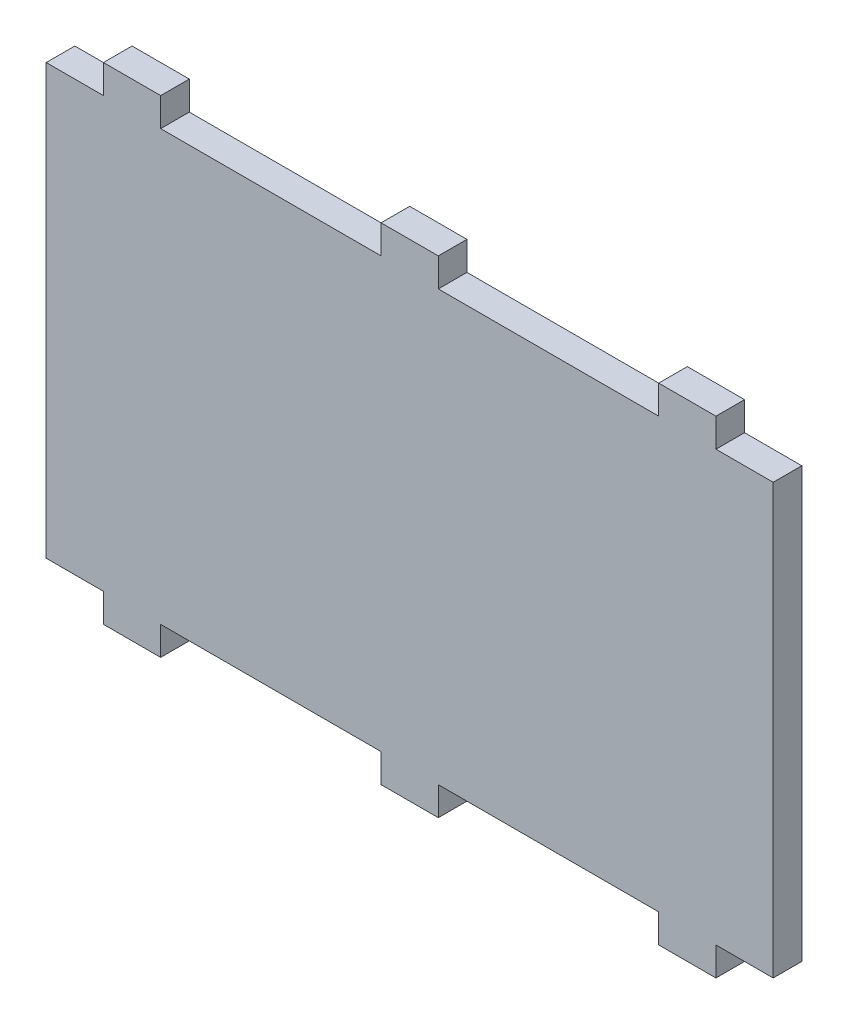
SolidWorks part; units mm, degrees
ref_plane "Plan de face" through (0, 0, 0) normal (0, 0, 1) x (1, 0, 0)
ref_plane "Plan de dessus" through (0, 0, 0) normal (0, 1, 0) x (1, 0, 0)
ref_plane "Plan de droite" through (0, 0, 0) normal (1, 0, 0) x (0, 0, -1)
sketch "Esquisse1" plane through (0, 0, 0) normal (0, 0, 1) x (1, 0, 0)
  line L1 (0, 0) -> (127, 0)
  line L2 (0, 0) -> (0, 75)
  line L3 (0, 75) -> (127, 75)
  line L4 (127, 0) -> (127, 75)
  dimension "D1" = 75
  dimension "D2" = 127
extrude "Boss.-Extru.1" add sketch "Esquisse1" along normal blind 5
sketch "Esquisse2" plane through (0, 0, 5) normal (0, 0, 1) x (1, 0, 0)
  line L0 (127, 75) -> (0, 75) construction
  line L1 (10, 75) -> (20, 75)
  line L2 (10, 75) -> (10, 80)
  line L3 (10, 80) -> (20, 80)
  line L4 (20, 75) -> (20, 80)
  line L5 (0, 0) -> (127, 0) construction
  line L6 (117, 75) -> (107, 75)
  line L7 (117, 75) -> (117, 80)
  line L8 (117, 80) -> (107, 80)
  line L9 (107, 75) -> (107, 80)
  line L10 (58.5, 75) -> (68.5, 75)
  line L11 (58.5, 75) -> (58.5, 80)
  line L12 (58.5, 80) -> (68.5, 80)
  line L13 (68.5, 75) -> (68.5, 80)
  line L14 (63.5, 75) -> (63.5, 0) construction
  line L18 (10, 0) -> (20, 0)
  line L19 (10, 0) -> (10, -5)
  line L20 (10, -5) -> (20, -5)
  line L21 (20, 0) -> (20, -5)
  line L22 (0, 75) -> (0, 0) construction
  line L23 (58.5, 0) -> (68.5, 0)
  line L24 (58.5, 0) -> (58.5, -5)
  line L25 (58.5, -5) -> (68.5, -5)
  line L26 (68.5, 0) -> (68.5, -5)
  line L31 (107, 0) -> (117, 0)
  line L32 (107, 0) -> (107, -5)
  line L33 (107, -5) -> (117, -5)
  line L34 (117, 0) -> (117, -5)
  line L35 (127, 0) -> (127, 75) construction
  dimension "D1" = 10
  dimension "D2" = 5
  dimension "D3" = 10
  dimension "D4" = 10
  dimension "D7" = 10
  dimension "D10" = 10
extrude "Boss.-Extru.2" add sketch "Esquisse2" against normal blind 5
